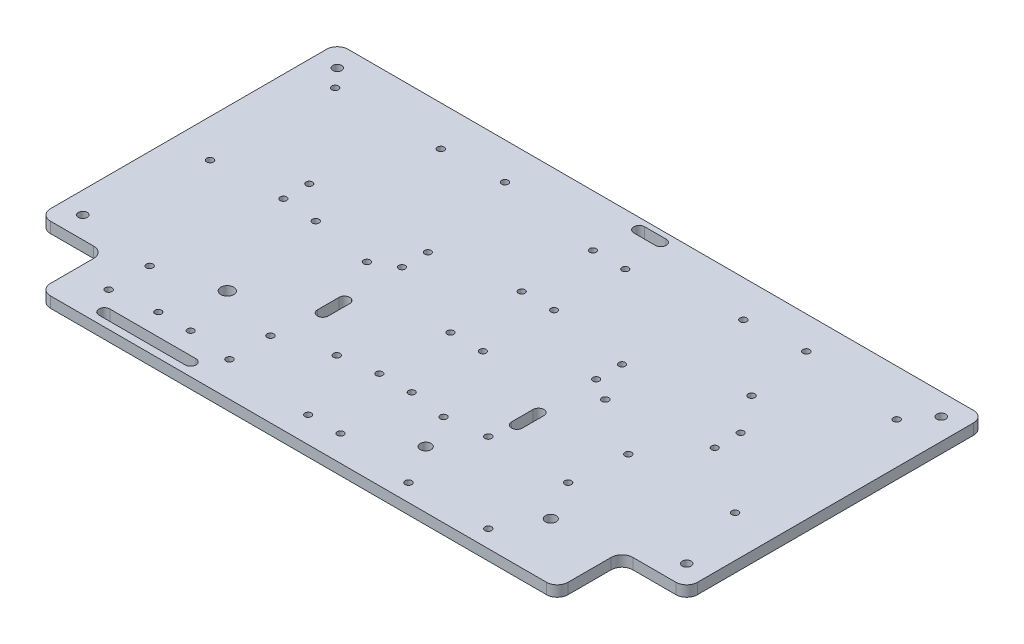
SolidWorks part; units mm, degrees
ref_plane "Plan de face" through (0, 0, 0) normal (0, 0, 1) x (1, 0, 0)
ref_plane "Plan de dessus" through (0, 0, 0) normal (0, 1, 0) x (1, 0, 0)
ref_plane "Plan de droite" through (0, 0, 0) normal (1, 0, 0) x (0, 0, -1)
sketch "Esquisse1" plane through (0, 0, 0) normal (0, 1, 0) x (1, 0, 0)
  line L0 (0, 81.3484) -> (0, -60.6791) construction
  line L1 (-137.8937, 0) -> (185.4331, 0) construction
  line L4 (150, -69) -> (150, 69)
  line L6 (-150, -69) -> (-150, 69)
  line L7 (150, -69) -> (-150, 69) construction
  line L8 (150, 69) -> (-150, -69) construction
  line L13 (80, -48.6) -> (80, 59) construction
  line L18 (-149.8488, 69) -> (-150, 69)
  line L22 (80, 59) -> (133.34, 59) construction
  line L23 (133.34, 59) -> (133.34, -48.6) construction
  line L24 (-104, -64) -> (-48, -64) construction
  line L25 (-104, -64) -> (-104, -83) construction
  line L26 (-104, -83) -> (-48, -83) construction
  line L27 (-48, -64) -> (-48, -83) construction
  line L28 (-104, -64) -> (-48, -83) construction
  line L29 (-104, -83) -> (-48, -64) construction
  line L35 (-132.5, 50.5) -> (-83.5, 50.5) construction
  line L40 (-76, -86) -> (-76, -93) construction
  line L46 (-56, -93) -> (-96, -93) construction
  line L47 (-56, -95.5) -> (-96, -95.5)
  line L53 (133.34, -48.6) -> (80, -48.6) construction
  line L54 (-136, 54) -> (-80, 54) construction
  line L55 (-136, 54) -> (-136, -34) construction
  line L56 (-136, -34) -> (-80, -34) construction
  line L57 (-80, 54) -> (-80, -34) construction
  line L58 (-136, 54) -> (-80, -34) construction
  line L59 (-136, -34) -> (-80, 54) construction
  line L60 (-107, -61) -> (-45, -61) construction
  line L61 (-107, -61) -> (-107, -86) construction
  line L62 (-107, -86) -> (-45, -86) construction
  line L63 (-45, -61) -> (-45, -86) construction
  line L64 (-107, -61) -> (-45, -86) construction
  line L65 (-107, -86) -> (-45, -61) construction
  line L66 (82.54, -48.6) -> (82.54, 59) construction
  line L67 (130.8, -48.6) -> (130.8, 59) construction
  line L68 (80, -42.6) -> (133.34, -42.6) construction
  line L69 (87.62, 23.44) -> (87.62, 59) construction
  line L71 (-120, -99) -> (120, -99)
  line L72 (120, -99) -> (120, -69)
  line L73 (-149.8488, 69) -> (150, 69)
  line L75 (120, -69) -> (150, -69)
  line L76 (-150, -69) -> (150, -69) construction
  line L77 (-150, -69) -> (-120, -69)
  line L78 (-120, -69) -> (-120, -99)
  line L79 (-63.25, 59) -> (-63.25, -19) construction
  line L80 (-63.25, -19) -> (-29.75, -19) construction
  line L81 (-29.75, -19) -> (-29.75, -61.5) construction
  line L82 (-29.75, -61.5) -> (29.75, -61.5) construction
  line L83 (29.75, -61.5) -> (29.75, -19) construction
  line L84 (29.75, -19) -> (63.25, -19) construction
  line L85 (63.25, -19) -> (63.25, 59) construction
  line L86 (63.25, 59) -> (-63.25, 59) construction
  line L87 (-83.5, 50.5) -> (-83.5, -7.5) construction
  line L88 (43, -54) -> (80, -54) construction
  line L89 (43, -54) -> (43, -91) construction
  line L90 (43, -91) -> (80, -91) construction
  line L91 (80, -54) -> (80, -91) construction
  line L92 (43, -54) -> (80, -91) construction
  line L93 (43, -91) -> (80, -54) construction
  line L94 (40, -51) -> (83, -51) construction
  line L95 (40, -51) -> (40, -94) construction
  line L96 (40, -94) -> (83, -94) construction
  line L97 (83, -51) -> (83, -94) construction
  line L98 (40, -51) -> (83, -94) construction
  line L99 (40, -94) -> (83, -51) construction
  line L100 (-83.5, -7.5) -> (-132.5, -7.5) construction
  line L101 (-132.5, -7.5) -> (-132.5, 50.5) construction
  line L102 (-108, 54) -> (-108, -34) construction
  line L103 (0, -61.5) -> (0, 59) construction
  line L104 (-63.25, 20) -> (63.25, 20) construction
  line L105 (-55.25, 52) -> (55.25, 52) construction
  line L106 (-55.25, 52) -> (-55.25, -12) construction
  line L107 (-55.25, -12) -> (55.25, -12) construction
  line L108 (55.25, 52) -> (55.25, -12) construction
  line L109 (-55.25, 52) -> (55.25, -12) construction
  line L110 (-55.25, -12) -> (55.25, 52) construction
  line L111 (-29.75, -56.5) -> (29.75, -56.5) construction
  line L112 (-56, -90.5) -> (-96, -90.5)
  line L113 (32.5, -72.5) -> (90.5, -72.5) construction
  line L114 (-5, 64) -> (5, 64) construction
  line L115 (-5, 66.5) -> (5, 66.5)
  line L116 (-5, 61.5) -> (5, 61.5)
  line L117 (-45, -37.7091) -> (48.5817, -37.7091) construction
  line L118 (-45, -32.7091) -> (-45, -42.7091) construction
  line L119 (-42.5, -32.7091) -> (-42.5, -42.7091)
  line L120 (-47.5, -32.7091) -> (-47.5, -42.7091)
  line L121 (45, -32.7091) -> (45, -42.7091) construction
  line L122 (42.5, -32.7091) -> (42.5, -42.7091)
  line L123 (47.5, -32.7091) -> (47.5, -42.7091)
  line L124 (-76, -61) -> (-76, -56) construction
  circle A0 centre (-140, 59) radius 2.05
  circle A1 centre (140, 59) radius 2.05
  circle A2 centre (140, -59) radius 2.05
  circle A3 centre (-140, -59) radius 2.05
  circle A19 centre (-48, -83) radius 1.55
  circle A20 centre (-104, -83) radius 1.55
  circle A21 centre (-48, -64) radius 1.55
  circle A22 centre (-104, -64) radius 1.55
  circle A27 centre (82.54, -28.63) radius 1.55
  circle A28 centre (130.8, -27.36) radius 1.55
  circle A29 centre (130.8, 47.57) radius 1.55
  circle A30 centre (82.54, 53.92) radius 1.55
  circle A31 centre (87.62, 23.44) radius 1.55
  circle A32 centre (43, -54) radius 1.55
  circle A33 centre (80, -54) radius 1.55
  circle A34 centre (80, -91) radius 1.55
  circle A35 centre (43, -91) radius 1.55
  circle A36 centre (-132.5, 50.5) radius 1.55
  circle A37 centre (-132.5, -7.5) radius 1.55
  circle A38 centre (-83.5, -7.5) radius 1.55
  circle A39 centre (-83.5, 50.5) radius 1.55
  circle A40 centre (-55.25, 52) radius 1.55
  circle A41 centre (-55.25, -12) radius 1.55
  circle A42 centre (55.25, 52) radius 1.55
  circle A43 centre (55.25, -12) radius 1.55
  circle A44 centre (-24.75, -56.5) radius 1.55
  circle A45 centre (24.75, -56.5) radius 1.55
  arc A46 (-56, -95.5) -> (-56, -90.5) centre (-56, -93) ccw
  arc A47 (-96, -90.5) -> (-96, -95.5) centre (-96, -93) ccw
  circle A48 centre (32.5, -72.5) radius 2.5
  circle A49 centre (90.5, -72.5) radius 2.5
  arc A50 (-5, 66.5) -> (-5, 61.5) centre (-5, 64) ccw
  arc A51 (5, 61.5) -> (5, 66.5) centre (5, 64) ccw
  arc A52 (-42.5, -32.7091) -> (-47.5, -32.7091) centre (-45, -32.7091) ccw
  arc A53 (-47.5, -42.7091) -> (-42.5, -42.7091) centre (-45, -42.7091) ccw
  arc A54 (42.5, -32.7091) -> (47.5, -32.7091) centre (45, -32.7091) cw
  arc A55 (47.5, -42.7091) -> (42.5, -42.7091) centre (45, -42.7091) cw
  circle A56 centre (-76, -56) radius 3
  point P1 (0, 0)
  point P21 (-76, -73.5)
  point P35 (0, 100)
  point P45 (-76, -93)
  point P61 (-76, -73.5)
  point P95 (61.5, -72.5)
  point P102 (61.5, -72.5)
  point P111 (40, -72.5)
  point P114 (0, 20)
  point P131 (0, 64)
  point P140 (-45, -37.7091)
  point P147 (45, -37.7091)
  dimension "D5" = 4.1
  dimension "D6" = 130
  dimension "D7" = 138
  dimension "D8" = 140
  dimension "D11" = 10
  dimension "D9" = 10
  dimension "D13" = 7.5
  dimension "D19" = 50.8
  dimension "D20" = 3.1
  dimension "D25" = 7.62
  dimension "D41" = 3.1
  dimension "D48" = 3.1
  dimension "D59" = 3.1
  dimension "D60" = 49.5
  dimension "D62" = 5
  dimension "D69" = 6
  dimension "D4" = 150
  dimension "D10" = 5
  dimension "D12" = 40
  dimension "D14" = 6
  dimension "D15" = 10
  dimension "D16" = 101.6
  dimension "D17" = 53.34
  dimension "D18" = 2.54
  dimension "D21" = 96.52
  dimension "D22" = 90.17
  dimension "D23" = 13.97
  dimension "D24" = 15.24
  dimension "D26" = 66.04
  dimension "D27" = 3
  dimension "D28" = 3
  dimension "D29" = 25
  dimension "D30" = 62
  dimension "D31" = 10
  dimension "D32" = 30
  dimension "D33" = 30
  dimension "D34" = 45
  dimension "D35" = 80
  dimension "D36" = 7.5
  dimension "D37" = 43
  dimension "D38" = 43
  dimension "D39" = 3
  dimension "D40" = 3
  dimension "D42" = 40
  dimension "D43" = 120
  dimension "D44" = 88
  dimension "D45" = 56
  dimension "D46" = 3.5
  dimension "D47" = 58
  dimension "D49" = 49
  dimension "D50" = 3.5
  dimension "D51" = 15
  dimension "D52" = 80
  dimension "D53" = 126.5
  dimension "D54" = 59.5
  dimension "D55" = 78
  dimension "D56" = 42.5
  dimension "D57" = 64
  dimension "D58" = 110.5
  dimension "D61" = 44.5
  dimension "D63" = 5
  dimension "D64" = 5
  dimension "D65" = 10
  dimension "D66" = 10
  dimension "D67" = 5
  dimension "D68" = 45
  dimension "D70" = 5
extrude "Boss.-Extru.1" add sketch "Esquisse1" along normal blind 5
fillet "Congé2" radius 5 8 edges at (150, 2.5, -69) (-150, 2.5, -69) (-150, 2.5, 69) (150, 2.5, 69) (120, 2.5, 69) (120, 2.5, 99) (-120, 2.5, 69) (-120, 2.5, 99)
sketch "Esquisse2" plane through (0, 5, 0) normal (0, 1, 0) x (1, 0, 0)
  line L0 (0, 69) -> (0, -99) construction
  line L1 (-150, 0) -> (150, 0) construction
  line L2 (0, 46.3302) -> (0, 45) construction
  line L3 (0, 45) -> (-7.5, 45) construction
  line L4 (-76, -90.5) -> (-76, -75) construction
  line L5 (-56, -90.5) -> (-96, -90.5) construction
  line L8 (150, -64) -> (150, 64)
  line L9 (145, 69) -> (-145, 69)
  line L10 (-150, 64) -> (-150, -64)
  line L11 (-145, -69) -> (-125, -69)
  line L12 (-120, -74) -> (-120, -94)
  line L13 (-115, -99) -> (115, -99)
  line L14 (120, -94) -> (120, -74)
  line L15 (125, -69) -> (145, -69)
  line L16 (150, -64) -> (150, 64)
  line L17 (145, 69) -> (-145, 69)
  line L18 (-150, 64) -> (-150, -64)
  line L19 (-145, -69) -> (-125, -69)
  line L20 (-120, -74) -> (-120, -94)
  line L21 (-115, -99) -> (115, -99)
  line L22 (120, -94) -> (120, -74)
  line L23 (125, -69) -> (145, -69)
  circle A0 centre (-7.5, 45) radius 1.5
  circle A1 centre (7.5, 45) radius 1.5
  circle A2 centre (-7.5, 12) radius 1.5
  circle A3 centre (7.5, 12) radius 1.5
  circle A4 centre (-7.5, -21) radius 1.5
  circle A5 centre (7.5, -21) radius 1.5
  circle A6 centre (-7.5, -54) radius 1.5
  circle A7 centre (7.5, -54) radius 1.5
  arc A8 (150, 64) -> (145, 69) centre (145, 64) ccw
  arc A9 (-145, 69) -> (-150, 64) centre (-145, 64) ccw
  arc A10 (-150, -64) -> (-145, -69) centre (-145, -64) ccw
  arc A11 (-120, -74) -> (-125, -69) centre (-125, -74) ccw
  arc A12 (-120, -94) -> (-115, -99) centre (-115, -94) ccw
  arc A13 (115, -99) -> (120, -94) centre (115, -94) ccw
  arc A14 (125, -69) -> (120, -74) centre (125, -74) ccw
  arc A15 (145, -69) -> (150, -64) centre (145, -64) ccw
  arc A16 (150, 64) -> (145, 69) centre (145, 64) ccw
  arc A17 (-145, 69) -> (-150, 64) centre (-145, 64) ccw
  arc A18 (-150, -64) -> (-145, -69) centre (-145, -64) ccw
  arc A19 (-120, -74) -> (-125, -69) centre (-125, -74) ccw
  arc A20 (-120, -94) -> (-115, -99) centre (-115, -94) ccw
  arc A21 (115, -99) -> (120, -94) centre (115, -94) ccw
  arc A22 (125, -69) -> (120, -74) centre (125, -74) ccw
  arc A23 (145, -69) -> (150, -64) centre (145, -64) ccw
  circle A24 centre (-7.5, -87) radius 1.5
  circle A25 centre (7.5, -87) radius 1.5
  circle A26 centre (-100, 6) radius 1.5
  circle A27 centre (-100, -6) radius 1.5
  circle A28 centre (100, -6) radius 1.5
  circle A29 centre (100, 6) radius 1.5
  circle A30 centre (-83.5, -80.5) radius 1.5
  circle A31 centre (-68.5, -80.5) radius 1.5
  circle A32 centre (-45, -6) radius 1.5
  circle A33 centre (-45, 6) radius 1.5
  circle A34 centre (45, 6) radius 1.5
  circle A35 centre (45, -6) radius 1.5
  dimension "D2" = 3
  dimension "D6" = 6
  dimension "D7" = 3
  dimension "D10" = 7.5
  dimension "D11" = 3
  dimension "D3" = 7.5
  dimension "D4" = 45
  dimension "D8" = 100
  dimension "D9" = 33
  dimension "D12" = 10
  dimension "D14" = 55
  dimension "D1" = 0
  dimension "D5" = 5
  dimension "D13" = 2
  dimension "D15" = 2
extrude "Enlèv. mat.-Extru.1" cut sketch "Esquisse2" against normal blind 10 contours A0 | A1 | A3 | A2 | A4 | A5 | A6 | A7 | A24 | A25 | A27 | A26 | A28 | A29 | A31 | A30 | A32 | A33 | A35 | A34
